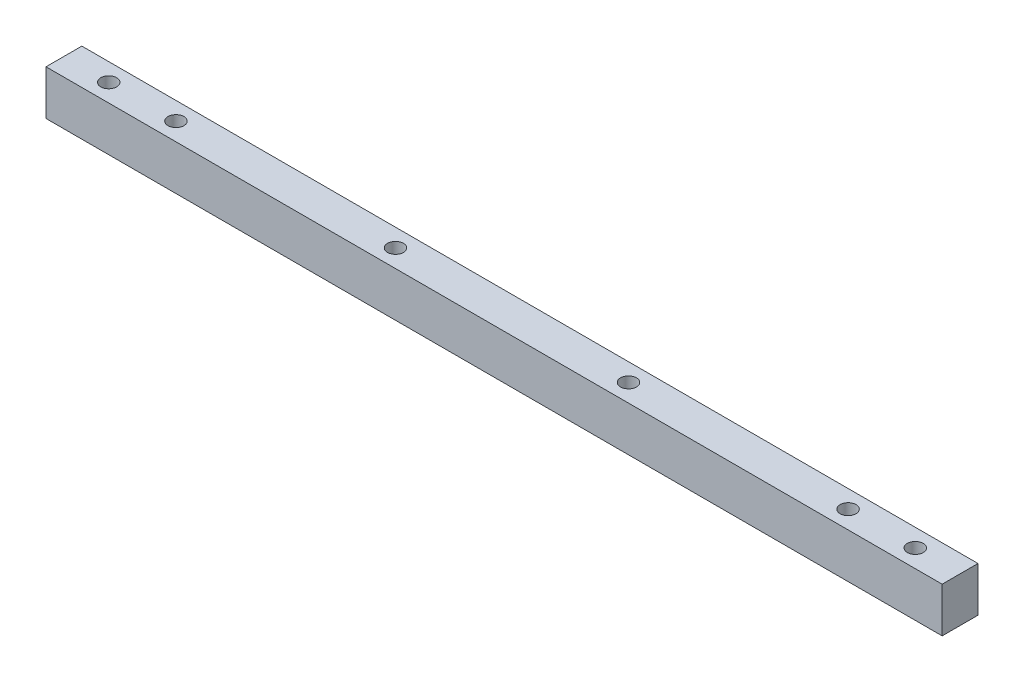
SolidWorks part; units mm, degrees
ref_plane "Front Plane" through (0, 0, 0) normal (0, 0, 1) x (1, 0, 0)
ref_plane "Top Plane" through (0, 0, 0) normal (0, 1, 0) x (1, 0, 0)
ref_plane "Right Plane" through (0, 0, 0) normal (1, 0, 0) x (0, 0, -1)
sketch "Sketch1" plane through (0, 0, 0) normal (0, 1, 0) x (1, 0, 0)
  line L1 (-93.5053, 4.2037) -> (106.4947, 4.2037)
  line L2 (-93.5053, 4.2037) -> (-93.5053, -3.7963)
  line L3 (-93.5053, -3.7963) -> (106.4947, -3.7963)
  line L4 (106.4947, 4.2037) -> (106.4947, -3.7963)
  dimension "D1" = 200
  dimension "D2" = 8
extrude "Boss-Extrude1" add sketch "Sketch1" along normal blind 10
sketch "Sketch2" plane through (0, 10, 0) normal (0, 1, 0) x (1, 0, 0)
  line L0 (-19.5053, 0.2037) -> (-93.5053, 0.2037) construction
  line L3 (-93.5053, 4.2037) -> (-93.5053, -3.7963) construction
  line L4 (32.4947, 0.2037) -> (106.4947, 0.2037) construction
  line L5 (106.4947, -3.7963) -> (106.4947, 4.2037) construction
  circle A0 centre (-19.5053, 0.2037) radius 1.775
  circle A1 centre (32.4947, 0.2037) radius 1.775
  dimension "D1" = 3.55
  dimension "D2" = 52
extrude "Cut-Extrude1" cut sketch "Sketch2" against normal through all
sketch "Sketch3" plane through (0, 10, 0) normal (0, 1, 0) x (1, 0, 0)
  line L0 (-93.5053, 0.2037) -> (-83.5053, 0.2037) construction
  line L1 (-93.5053, 4.2037) -> (-93.5053, -3.7963) construction
  line L2 (-83.5053, 0.2037) -> (-68.5053, 0.2037) construction
  line L4 (81.4947, 0.2037) -> (96.4947, 0.2037) construction
  line L5 (96.4947, 0.2037) -> (106.4947, 0.2037) construction
  line L6 (106.4947, -3.7963) -> (106.4947, 4.2037) construction
  circle A0 centre (-83.5053, 0.2037) radius 1.775
  circle A1 centre (-68.5053, 0.2037) radius 1.775
  circle A2 centre (81.4947, 0.2037) radius 1.775
  circle A3 centre (96.4947, 0.2037) radius 1.775
  dimension "D3" = 3.55
  dimension "D1" = 10
  dimension "D2" = 25
extrude "Cut-Extrude2" cut sketch "Sketch3" against normal through all
